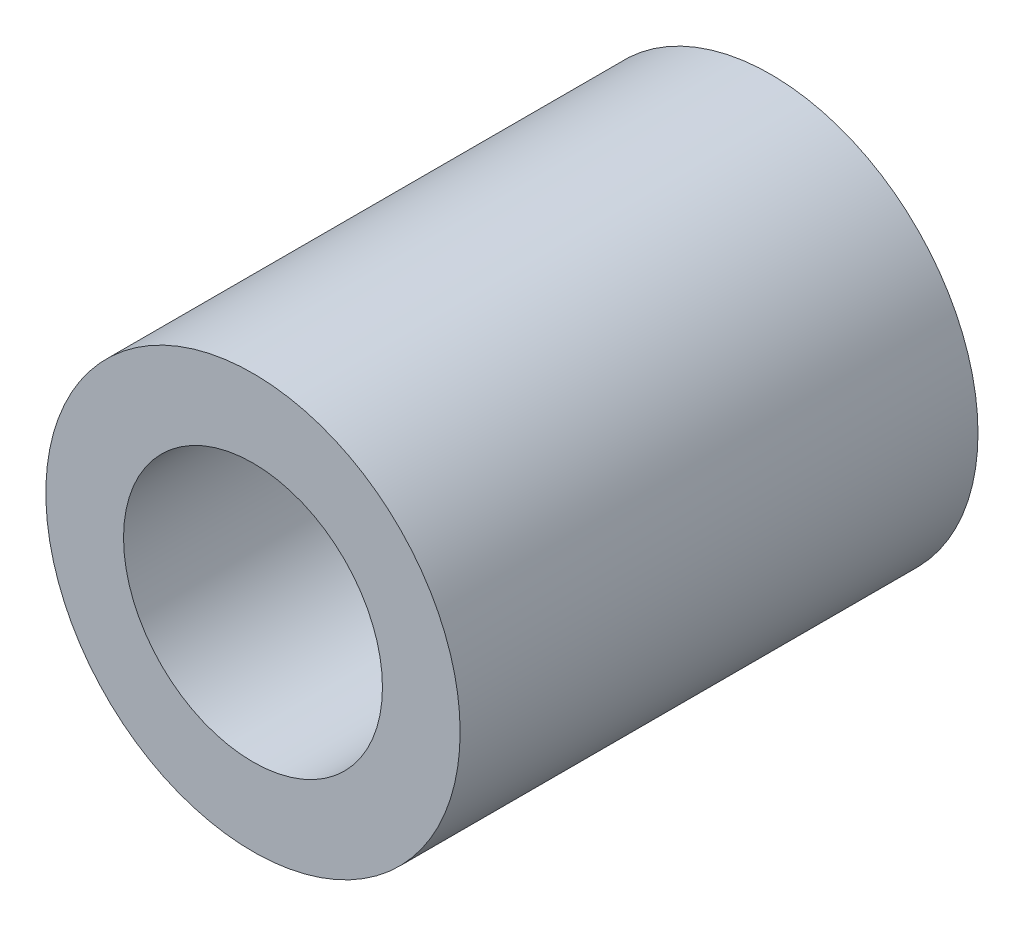
SolidWorks part; units mm, degrees
ref_plane "前视基准面" through (0, 0, 0) normal (0, 0, 1) x (1, 0, 0)
ref_plane "上视基准面" through (0, 0, 0) normal (0, 1, 0) x (1, 0, 0)
ref_plane "右视基准面" through (0, 0, 0) normal (1, 0, 0) x (0, 0, -1)
other "Configuration Table"
sketch "草图1" plane through (0, 0, 0) normal (0, 0, 1) x (1, 0, 0)
  circle A0 centre (0, 0) radius 2
  circle A1 centre (0, 0) radius 1.25
extrude "Knurl_OD4_length5_M3_thread_envelope" add sketch "草图1" along normal blind 5
